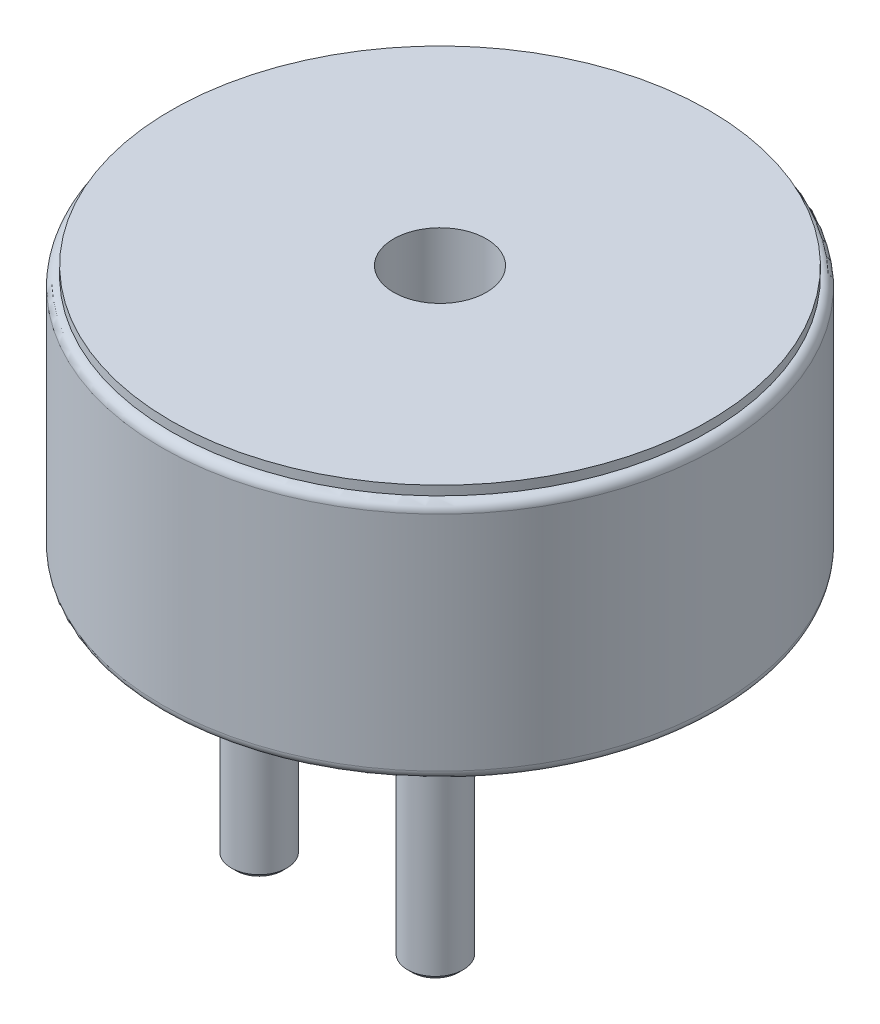
SolidWorks part; units mm, degrees
ref_plane "Front Plane" through (0, 0, 0) normal (0, 0, 1) x (1, 0, 0)
ref_plane "Top Plane" through (0, 0, 0) normal (0, 1, 0) x (1, 0, 0)
ref_plane "Right Plane" through (0, 0, 0) normal (1, 0, 0) x (0, 0, -1)
sketch "Sketch1" plane through (0, 0, 0) normal (0, 1, 0) x (1, 0, 0)
  circle A0 centre (0, 0) radius 3
  dimension "D1" = 6
extrude "Boss-Extrude1" add sketch "Sketch1" along normal blind 2.6
fillet "Fillet1" radius 0.1 2 edges at (0, 2.6, 3) (0, 0, 3)
sketch "Sketch3" plane through (0, 2.6, 0) normal (0, 1, 0) x (1, 0, 0)
  circle A1 centre (0, 0) radius 2.9
  circle A2 centre (0, 0) radius 2.9
  dimension "D1" = 0
extrude "Boss-Extrude2" add sketch "Sketch3" along normal blind 0.1
sketch "Sketch2" plane through (0, 2.7, 0) normal (0, 1, 0) x (1, 0, 0)
  circle A0 centre (0, 0) radius 0.5
  dimension "D1" = 1
extrude "Cut-Extrude1" cut sketch "Sketch2" against normal blind 1
sketch "Sketch4" plane through (0, 0, 0) normal (0, -1, 0) x (1, 0, 0)
  line L0 (-2.9, 0) -> (2.9, 0) construction
  line L1 (0, 2.9) -> (0, -2.9) construction
  line L2 (-2.7221, 1) -> (2.7221, 1) construction
  circle A0 centre (0, 0) radius 2.9 construction
  circle A1 centre (-0.95, 1) radius 0.3
  circle A2 centre (0.95, 1) radius 0.3
  dimension "D3" = 0.6
  dimension "D1" = 1
  dimension "D2" = 1.9
extrude "Boss-Extrude3" add sketch "Sketch4" along normal blind 2.8
chamfer "Chamfer1" distance 0.05 angle 45 2 edges at (0.95, -2.8, 1.3) (-0.95, -2.8, 0.7)
